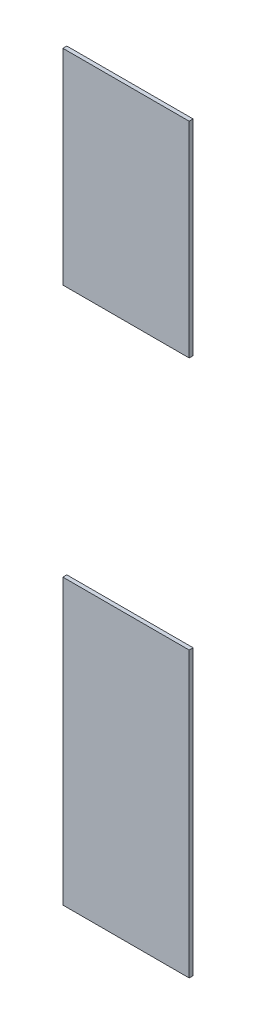
SolidWorks part; units mm, degrees
material "Гипс"
ref_plane "Спереди" through (0, 0, 0) normal (0, 0, 1) x (1, 0, 0)
ref_plane "Сверху" through (0, 0, 0) normal (0, 1, 0) x (1, 0, 0)
ref_plane "Справа" through (0, 0, 0) normal (1, 0, 0) x (0, 0, -1)
sketch "Эскиз1" plane through (0, 0, 0) normal (0, 0, 1) x (1, 0, 0)
  line L0 (800, -1450) -> (0, -1450) construction
  line L1 (0, 0) -> (400, 0)
  line L2 (0, 0) -> (0, -649.25)
  line L3 (0, -649.25) -> (400, -649.25)
  line L4 (400, 0) -> (400, -649.25)
  line L5 (0, -2349.25) -> (400, -2349.25)
  line L6 (0, -2349.25) -> (0, -1450)
  line L7 (0, -1450) -> (400, -1450)
  line L8 (400, -2349.25) -> (400, -1450)
extrude "Бобышка-Вытянуть1" add sketch "Эскиз1" along normal blind 12.5
